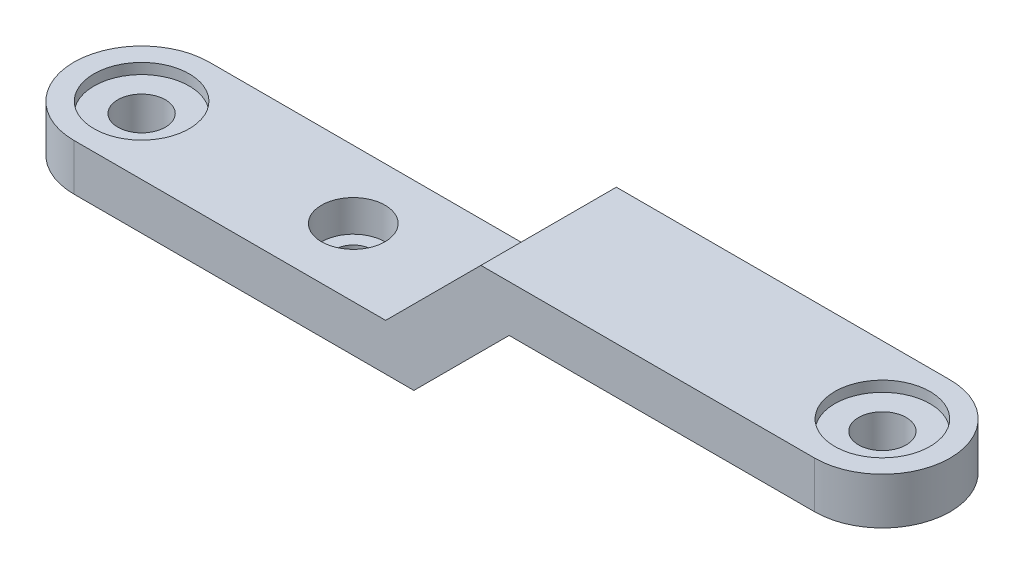
SolidWorks part; units mm, degrees
ref_plane "前视基准面" through (0, 0, 0) normal (0, 0, 1) x (1, 0, 0)
ref_plane "上视基准面" through (0, 0, 0) normal (0, 1, 0) x (1, 0, 0)
ref_plane "右视基准面" through (0, 0, 0) normal (1, 0, 0) x (0, 0, -1)
other "Configuration Table"
sketch "草图1" plane through (0, 0, 0) normal (0, 0, 1) x (1, 0, 0)
  line L0 (0, 0) -> (38.5311, 0)
  line L1 (38.5311, 0) -> (47.5311, 9)
  line L2 (47.5311, 9) -> (82.8, 9)
  line L3 (82.8, 9) -> (82.8, 13.4)
  line L4 (82.8, 13.4) -> (44.86, 13.4)
  line L5 (44.86, 13.4) -> (35.86, 4.4)
  line L6 (35.86, 4.4) -> (0, 4.4)
  line L7 (0, 0) -> (0, 4.4)
  point P3 (0.7367, 11.4765)
  dimension "D1" = 82.8
  dimension "D2" = 4.4
  dimension "D3" = 4.4
  dimension "D4" = 135
  dimension "D5" = 9
  dimension "D6" = 5
  dimension "D7" = 35.86
extrude "凸台-拉伸1" add sketch "草图1" along normal mid plane 12.8
sketch "草图2" plane through (0, 13.4, 0) normal (0, 1, 0) x (1, 0, 0)
  line L0 (82.8, 6.4) -> (44.86, 6.4) construction
  line L1 (44.86, -6.4) -> (82.8, -6.4) construction
  line L3 (44.86, 6.4) -> (35.86, 6.4) construction
  line L4 (35.86, -6.4) -> (44.86, -6.4) construction
  line L5 (35.86, 6.4) -> (0, 6.4) construction
  line L7 (0, -6.4) -> (35.86, -6.4) construction
  line L8 (76.4, 6.4) -> (44.86, 6.4)
  line L9 (44.86, -6.4) -> (76.4, -6.4)
  line L11 (44.86, 6.4) -> (35.86, 6.4)
  line L12 (35.86, -6.4) -> (44.86, -6.4)
  line L13 (35.86, 6.4) -> (6.4, 6.4)
  line L15 (6.4, -6.4) -> (35.86, -6.4)
  line L16 (0, 0) -> (23.8795, 0) construction
  arc A1 (6.4, 6.4) -> (6.4, -6.4) centre (6.4, 0) ccw
  arc A2 (76.4, -6.4) -> (76.4, 6.4) centre (76.4, 0) ccw
extrude "切除-拉伸1" cut sketch "草图2" against normal through all flip side to cut
sketch "草图3" plane through (0, 4.4, 0) normal (0, 1, 0) x (1, 0, 0)
  circle A0 centre (6.4, 0) radius 2.25
  circle A1 centre (76.4, 0) radius 2.25
  dimension "D1" = 4.5
extrude "切除-拉伸2" cut sketch "草图3" against normal through all both and the other way through all
sketch "草图4" plane through (0, 13.4, 0) normal (0, 1, 0) x (1, 0, 0)
  circle A0 centre (76.4, 0) radius 4.5
  dimension "D1" = 9
extrude "切除-拉伸3" cut sketch "草图4" against normal blind 1
sketch "草图5" plane through (0, 4.4, 0) normal (0, 1, 0) x (1, 0, 0)
  circle A0 centre (6.4, 0) radius 4.5
  dimension "D1" = 9
extrude "切除-拉伸4" cut sketch "草图5" against normal blind 1
sketch "草图6" plane through (0, 4.4, 0) normal (0, 1, 0) x (1, 0, 0)
  circle A0 centre (26.4, 0) radius 3
  circle A1 centre (6.4, 0) radius 2.25 construction
  dimension "D1" = 20
  dimension "D2" = 6
extrude "切除-拉伸5" cut sketch "草图6" against normal blind 3
sketch "草图7" plane through (0, 4.4, 0) normal (0, 1, 0) x (1, 0, 0)
  circle A0 centre (26.4, 0) radius 1.75
  dimension "D1" = 3.5
extrude "切除-拉伸6" cut sketch "草图7" against normal through all
